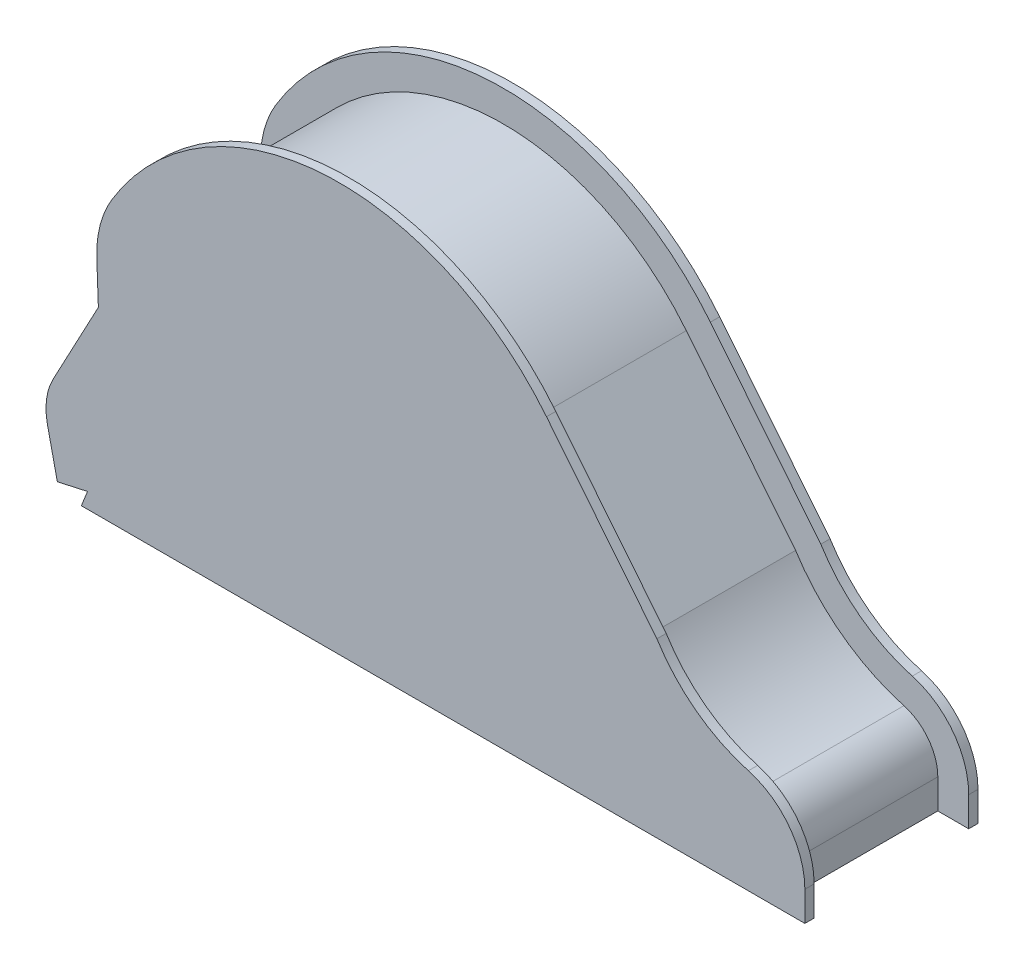
SolidWorks part; units mm, degrees
ref_plane "Ebene vorne" through (0, 0, 0) normal (0, 0, 1) x (1, 0, 0)
ref_plane "Ebene oben" through (0, 0, 0) normal (0, 1, 0) x (1, 0, 0)
ref_plane "Ebene rechts" through (0, 0, 0) normal (1, 0, 0) x (0, 0, -1)
sketch "Skizze2" plane through (0, 0, 0) normal (0, 0, 1) x (1, 0, 0)
  line L0 (0, 0) -> (112, 0)
  line L1 (112, 0) -> (112, 4.7828)
  line L2 (1, 2.5) -> (0, 0)
  line L3 (-0.5988, 9.6944) -> (1, 2.5)
  line L4 (-0.1296, 13.132) -> (7.8, 28)
  line L5 (7.8, 28) -> (7.4961, 36.104)
  line L7 (71.3299, 46.9372) -> (89, 25)
  arc A5 (-0.1296, 13.132) -> (-0.5988, 9.6944) centre (4.2822, 10.7791) ccw
  arc A6 (112, 4.7828) -> (106.5209, 12.0054) centre (104.5, 4.7828) ccw
  arc A7 (89, 25) -> (106.5209, 12.0054) centre (114.7475, 41.4067) ccw
  arc A8 (9.2191, 42.763) -> (7.4961, 36.104) centre (19.4877, 36.5536) ccw
  arc A9 (71.3299, 46.9372) -> (9.2191, 42.763) centre (41.7363, 23.1) ccw
extrude "Aufsatz-Linear austragen1" add sketch "Skizze2" against normal blind 28
sketch "Skizze3" plane through (0, 0, 0) normal (0, 0, 1) x (1, 0, 0)
  line L3 (93.0755, 27.911) -> (75.2239, 50.0737)
  line L4 (93.0755, 27.911) -> (75.2239, 50.0737)
  line L6 (117, 0) -> (117, 4.7828)
  line L7 (117, 0) -> (117, 4.7828)
  line L39 (-3.8809, 1.4153) -> (1, 2.5)
  line L40 (2.7529, 29.1617) -> (-4.5414, 15.485)
  line L41 (2.4996, 35.9166) -> (2.7529, 29.1617)
  line L42 (2.7529, 29.1617) -> (-4.5414, 15.485)
  line L43 (2.4996, 35.9166) -> (2.7529, 29.1617)
  line L44 (-5.4797, 8.6098) -> (-3.8809, 1.4153)
  line L45 (-5.4797, 8.6098) -> (-3.8809, 1.4153)
  line L46 (112, 0) -> (117, 0)
  line L47 (112, 0) -> (112, 4.7828) construction
  line L48 (112, 0) -> (112, 4.7828)
  line L49 (89, 25) -> (71.3299, 46.9372) construction
  line L50 (89, 25) -> (71.3299, 46.9372)
  line L51 (-0.5988, 9.6944) -> (1, 2.5) construction
  line L52 (7.4961, 36.104) -> (7.8, 28) construction
  line L53 (7.8, 28) -> (-0.1296, 13.132) construction
  line L54 (-0.5988, 9.6944) -> (1, 2.5)
  line L55 (7.4961, 36.104) -> (7.8, 28)
  line L56 (7.8, 28) -> (-0.1296, 13.132)
  arc A2 (75.2239, 50.0737) -> (4.9405, 45.3503) centre (41.7363, 23.1) ccw
  arc A3 (75.2239, 50.0737) -> (4.9405, 45.3503) centre (41.7363, 23.1) ccw
  arc A34 (93.0755, 27.911) -> (107.8682, 16.8204) centre (114.7475, 41.4067) ccw
  arc A35 (93.0755, 27.911) -> (107.8682, 16.8204) centre (114.7475, 41.4067) ccw
  arc A37 (117, 4.7828) -> (107.8682, 16.8204) centre (104.5, 4.7828) ccw
  arc A38 (117, 4.7828) -> (107.8682, 16.8204) centre (104.5, 4.7828) ccw
  arc A42 (4.9405, 45.3503) -> (2.4996, 35.9166) centre (19.4877, 36.5536) ccw
  arc A43 (4.9405, 45.3503) -> (2.4996, 35.9166) centre (19.4877, 36.5536) ccw
  arc A45 (112, 4.7828) -> (106.5209, 12.0054) centre (104.5, 4.7828) ccw construction
  arc A46 (-4.5414, 15.485) -> (-5.4797, 8.6098) centre (4.2822, 10.7791) ccw
  arc A47 (-4.5414, 15.485) -> (-5.4797, 8.6098) centre (4.2822, 10.7791) ccw
  arc A48 (89, 25) -> (106.5209, 12.0054) centre (114.7475, 41.4067) ccw construction
  arc A49 (112, 4.7828) -> (106.5209, 12.0054) centre (104.5, 4.7828) ccw
  arc A50 (89, 25) -> (106.5209, 12.0054) centre (114.7475, 41.4067) ccw
  arc A51 (71.3299, 46.9372) -> (9.2191, 42.763) centre (41.7363, 23.1) ccw construction
  arc A52 (71.3299, 46.9372) -> (9.2191, 42.763) centre (41.7363, 23.1) ccw
  arc A53 (-0.1296, 13.132) -> (-0.5988, 9.6944) centre (4.2822, 10.7791) ccw construction
  arc A54 (9.2191, 42.763) -> (7.4961, 36.104) centre (19.4877, 36.5536) ccw construction
  arc A55 (-0.1296, 13.132) -> (-0.5988, 9.6944) centre (4.2822, 10.7791) ccw
  arc A56 (9.2191, 42.763) -> (7.4961, 36.104) centre (19.4877, 36.5536) ccw
  dimension "D1" = 5
  dimension "D2" = 5
  dimension "D3" = 5
  dimension "D4" = 5
  dimension "D5" = 5
  dimension "D6" = 5
extrude "Aufsatz-Linear austragen2" add sketch "Skizze3" against normal blind 1.5
ref_plane "Ebene1" through (0, 0, -14) normal (0, 0, 1) x (1, 0, 0)
mirror "Spiegeln1" about plane through (0, 0, -14) normal (0, 0, 1) of "Aufsatz-Linear austragen2"
